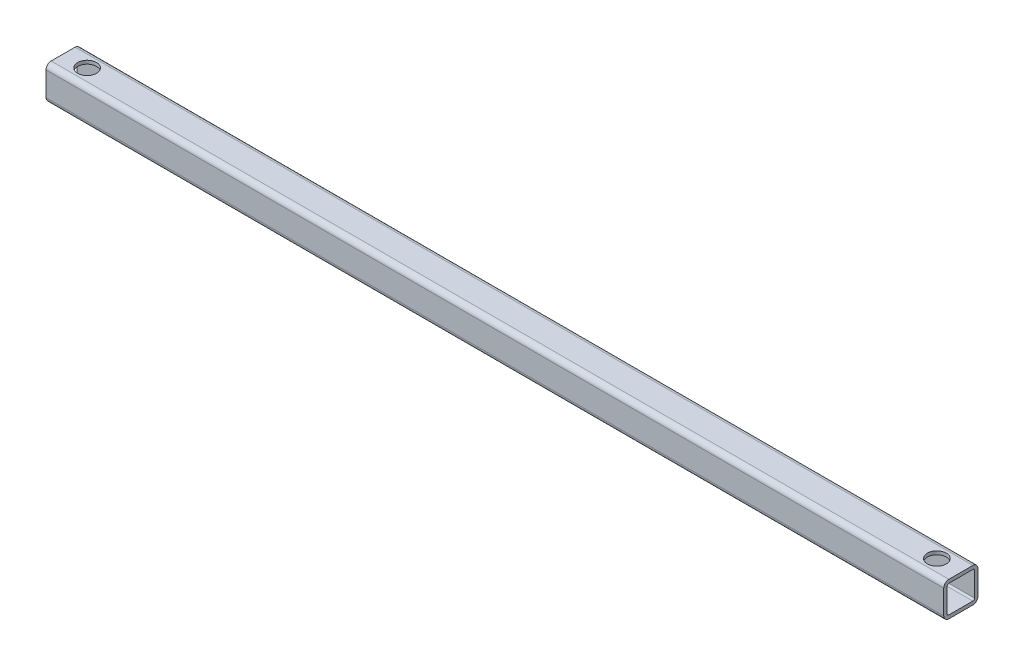
SolidWorks part; units mm, degrees
material "AISI 1020 Сталь, холоднокатаная"
ref_plane "Спереди" through (0, 0, 0) normal (0, 0, 1) x (1, 0, 0)
ref_plane "Сверху" through (0, 0, 0) normal (0, 1, 0) x (1, 0, 0)
ref_plane "Справа" through (0, 0, 0) normal (1, 0, 0) x (0, 0, -1)
sketch "Эскиз1" plane through (0, 0, 0) normal (0, 0, 1) x (1, 0, 0)
  line L0 (-262, 0) -> (262, 0)
  dimension "D1" = 524
other "Квадратная труба 20 X 20 X 2(1)"
ref_plane "Плоскость1" through (-262, 0, 0) normal (1, 0, 0) x (0, 1, 0)
sketch "Sketch1" plane through (-262, 0, 0) normal (1, 0, 0) x (0, 1, 0)
  line L0 (-7, -8) -> (7, -8)
  line L1 (-8, -7) -> (-8, 7)
  line L2 (7, 8) -> (-7, 8)
  line L3 (8, 7) -> (8, -7)
  line L4 (-7, -10) -> (7, -10)
  line L5 (-10, -7) -> (-10, 7)
  line L6 (7, 10) -> (-7, 10)
  line L7 (10, 7) -> (10, -7)
  arc A0 (10, 7) -> (7, 10) centre (7, 7) ccw
  arc A1 (7, -10) -> (10, -7) centre (7, -7) ccw
  arc A2 (-10, -7) -> (-7, -10) centre (-7, -7) ccw
  arc A3 (-7, 10) -> (-10, 7) centre (-7, 7) ccw
  arc A4 (-7, 8) -> (-8, 7) centre (-7, 7) ccw
  arc A5 (8, 7) -> (7, 8) centre (7, 7) ccw
  arc A6 (7, -8) -> (8, -7) centre (7, -7) ccw
  arc A7 (-8, -7) -> (-7, -8) centre (-7, -7) ccw
  point P0 (-10, 0)
  point P1 (10, 0)
  point P2 (0, 10)
  point P3 (0, -10)
  point P4 (0, 0)
  point P5 (-10, -10)
  point P6 (10, -10)
  point P7 (10, 10)
  point P8 (-10, 10)
  point P33 (0, 0)
  dimension "D1" = 3
  dimension "Thickness" = 2
  dimension "V_leg" = 20
sketch "Эскиз3" plane through (0, 10, 0) normal (0, 1, 0) x (1, 0, 0)
  line L0 (0, 51.4266) -> (0, -51.4266) construction
  line L1 (-262, 7) -> (-262, -7) construction
  circle A0 centre (-248, 0) radius 5.5
  circle A1 centre (248, 0) radius 5.5
  dimension "D1" = 11
  dimension "D2" = 14
extrude "Вырез-Вытянуть1" cut sketch "Эскиз3" against normal up to next
sketch "Эскиз4" plane through (0, -8, 0) normal (0, 1, 0) x (1, 0, 0)
  circle A0 centre (-248, 0) radius 2.5
  circle A1 centre (-248, 0) radius 5.5 construction
  circle A2 centre (248, 0) radius 2.5
  circle A3 centre (248, 0) radius 5.5 construction
  dimension "D1" = 5
  dimension "D2" = 5
extrude "Вырез-Вытянуть2" cut sketch "Эскиз4" against normal through all
